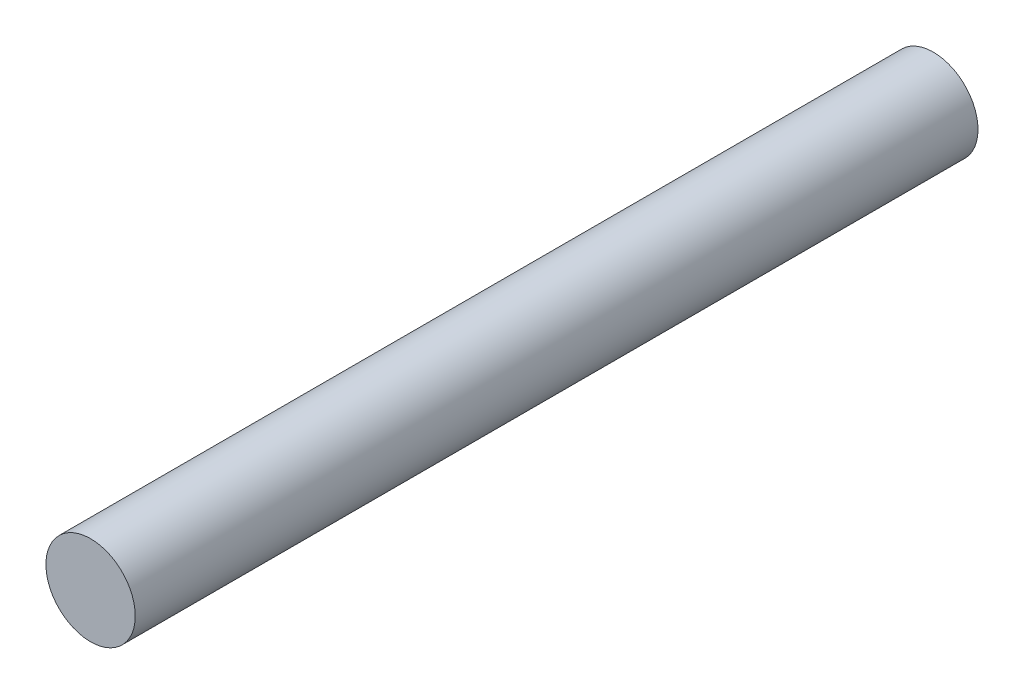
SolidWorks part; units mm, degrees
ref_plane "Front Plane" through (0, 0, 0) normal (0, 0, 1) x (1, 0, 0)
ref_plane "Top Plane" through (0, 0, 0) normal (0, 1, 0) x (1, 0, 0)
ref_plane "Right Plane" through (0, 0, 0) normal (1, 0, 0) x (0, 0, -1)
sketch "Sketch1" plane through (0, 0, 0) normal (0, 0, 1) x (1, 0, 0)
  circle A0 centre (0, 0) radius 15.9
extrude "Boss-Extrude1" add sketch "Sketch1" along normal blind 300
